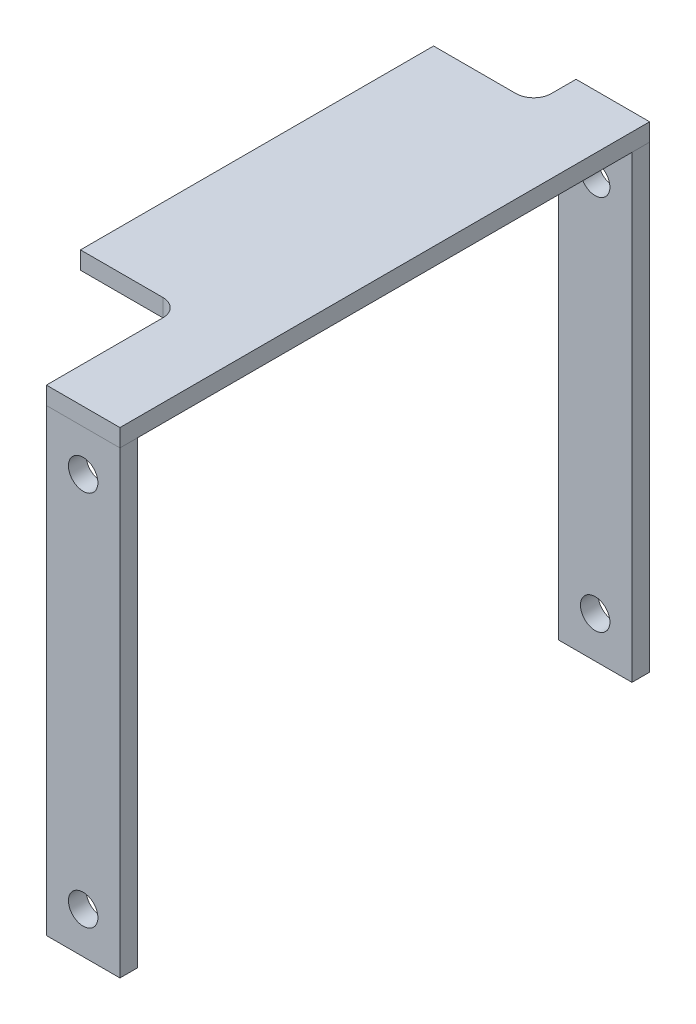
SolidWorks part; units mm, degrees
material "Plain Carbon Steel"
ref_plane "Front Plane" through (0, 0, 0) normal (0, 0, 1) x (1, 0, 0)
ref_plane "Top Plane" through (0, 0, 0) normal (0, 1, 0) x (1, 0, 0)
ref_plane "Right Plane" through (0, 0, 0) normal (1, 0, 0) x (0, 0, -1)
sketch "Sketch1" plane through (0, 0, 0) normal (1, 0, 0) x (0, 0, -1)
  line L0 (42, 78) -> (-42, 78)
  line L1 (-42, 78) -> (-42, 0)
  line L2 (-42, 0) -> (-45, 0)
  line L3 (-45, 0) -> (-45, 81)
  line L4 (-45, 81) -> (45, 81)
  line L5 (0, 0) -> (0, -25.7183) construction
  line L6 (45, 0) -> (45, 81)
  line L7 (42, 78) -> (42, 0)
  line L8 (42, 0) -> (45, 0)
  point P3 (43.5, 0)
  point P12 (0, 78)
  point P13 (0, 81)
  dimension "D1" = 3
  dimension "D2" = 84
  dimension "D3" = 3
  dimension "D4" = 78
extrude "Boss-Extrude1" add sketch "Sketch1" along normal blind 12.5
sketch "Sketch3" plane through (0, 0, 45) normal (0, 0, 1) x (1, 0, 0)
  line L0 (12.5, 0) -> (0, 0) construction
  circle A0 centre (6.25, 71) radius 2.5
  circle A1 centre (6.25, 7) radius 2.5
  point P6 (6.25, 0)
  dimension "D1" = 5
  dimension "D2" = 5
  dimension "D3" = 7
  dimension "D4" = 64
extrude "Cut-Extrude1" cut sketch "Sketch3" against normal through all and the other way through all
sketch "Sketch2" plane through (0, 81, 0) normal (0, 1, 0) x (1, 0, 0)
  line L0 (0, 37.794) -> (-17, 37.794)
  line L1 (0, 45) -> (0, -45) construction
  line L2 (-17, 37.794) -> (-17, -22.206)
  line L3 (-17, -22.206) -> (0, -22.206)
  line L4 (0, -22.206) -> (0, 37.794)
  dimension "D1" = 17
  dimension "D2" = 60
extrude "Boss-Extrude2" add sketch "Sketch2" against normal up to surface (3 mm away) up to face at (6.25, 78, 0)
fillet "Fillet1" radius 3 2 edges at (0, 79.5, 22.206) (0, 79.5, -37.794)
sketch "Sketch4" plane through (0, 0, 45) normal (0, 0, 1) x (1, 0, 0)
  line L0 (0, 78) -> (12.5, 78)
split line "Split Line1"
